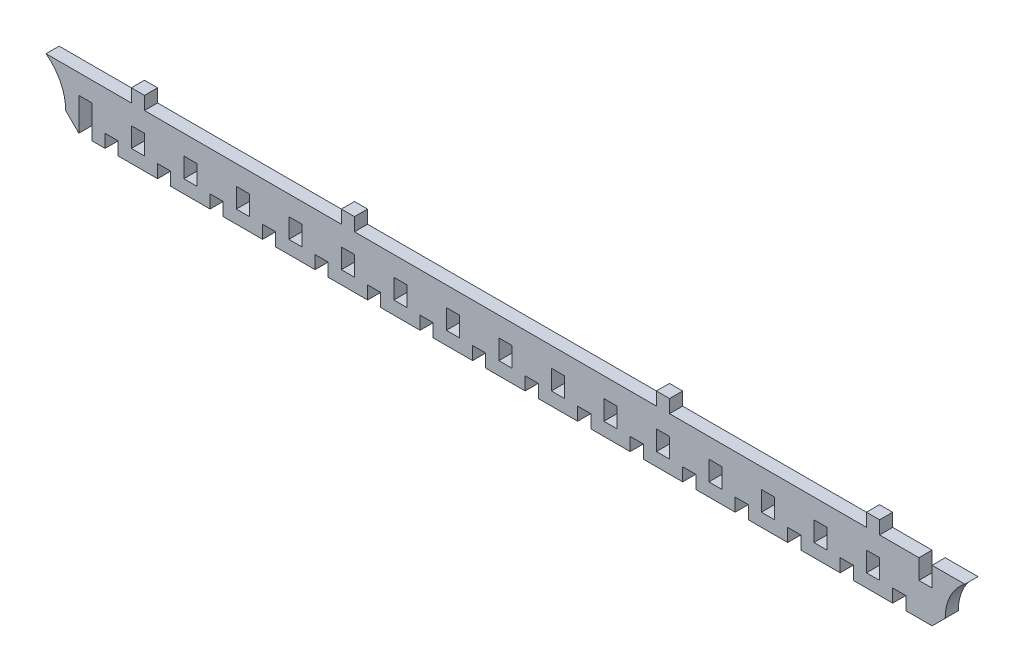
SolidWorks part; units mm, degrees
ref_plane "Front Plane" through (0, 0, 0) normal (0, 0, 1) x (1, 0, 0)
ref_plane "Top Plane" through (0, 0, 0) normal (0, 1, 0) x (1, 0, 0)
ref_plane "Right Plane" through (0, 0, 0) normal (1, 0, 0) x (0, 0, -1)
sketch "Sketch1" plane through (0, 0, 0) normal (0, 0, 1) x (1, 0, 0)
  line L151 (25.5, 6) -> (25.5, 10.5)
  line L152 (25.5, 10.5) -> (22.5, 10.5)
  line L153 (22.5, 10.5) -> (22.5, 6)
  line L154 (22.5, 6) -> (25.5, 6)
  line L155 (37.5, 6) -> (37.5, 10.5)
  line L156 (37.5, 10.5) -> (34.5, 10.5)
  line L157 (34.5, 10.5) -> (34.5, 6)
  line L158 (34.5, 6) -> (37.5, 6)
  line L159 (49.5, 6) -> (49.5, 10.5)
  line L160 (49.5, 10.5) -> (46.5, 10.5)
  line L161 (46.5, 10.5) -> (46.5, 6)
  line L162 (46.5, 6) -> (49.5, 6)
  line L163 (61.5, 6) -> (61.5, 10.5)
  line L164 (61.5, 10.5) -> (58.5, 10.5)
  line L165 (58.5, 10.5) -> (58.5, 6)
  line L166 (58.5, 6) -> (61.5, 6)
  line L167 (73.5, 6) -> (73.5, 10.5)
  line L168 (73.5, 10.5) -> (70.5, 10.5)
  line L169 (70.5, 10.5) -> (70.5, 6)
  line L170 (70.5, 6) -> (73.5, 6)
  line L171 (85.5, 6) -> (85.5, 10.5)
  line L172 (85.5, 10.5) -> (82.5, 10.5)
  line L173 (82.5, 10.5) -> (82.5, 6)
  line L174 (82.5, 6) -> (85.5, 6)
  line L175 (97.5, 6) -> (97.5, 10.5)
  line L176 (97.5, 10.5) -> (94.5, 10.5)
  line L177 (94.5, 10.5) -> (94.5, 6)
  line L178 (94.5, 6) -> (97.5, 6)
  line L179 (109.5, 6) -> (109.5, 10.5)
  line L180 (109.5, 10.5) -> (106.5, 10.5)
  line L181 (106.5, 10.5) -> (106.5, 6)
  line L182 (106.5, 6) -> (109.5, 6)
  line L183 (121.5, 6) -> (121.5, 10.5)
  line L184 (121.5, 10.5) -> (118.5, 10.5)
  line L185 (118.5, 10.5) -> (118.5, 6)
  line L186 (118.5, 6) -> (121.5, 6)
  line L187 (133.5, 6) -> (133.5, 10.5)
  line L188 (133.5, 10.5) -> (130.5, 10.5)
  line L189 (130.5, 10.5) -> (130.5, 6)
  line L190 (130.5, 6) -> (133.5, 6)
  line L191 (145.5, 6) -> (145.5, 10.5)
  line L192 (145.5, 10.5) -> (142.5, 10.5)
  line L193 (142.5, 10.5) -> (142.5, 6)
  line L194 (142.5, 6) -> (145.5, 6)
  line L195 (157.5, 6) -> (157.5, 10.5)
  line L196 (157.5, 10.5) -> (154.5, 10.5)
  line L197 (154.5, 10.5) -> (154.5, 6)
  line L198 (154.5, 6) -> (157.5, 6)
  line L199 (169.5, 6) -> (169.5, 10.5)
  line L200 (169.5, 10.5) -> (166.5, 10.5)
  line L201 (166.5, 10.5) -> (166.5, 6)
  line L202 (166.5, 6) -> (169.5, 6)
  line L203 (181.5, 6) -> (181.5, 10.5)
  line L204 (181.5, 10.5) -> (178.5, 10.5)
  line L205 (178.5, 10.5) -> (178.5, 6)
  line L206 (178.5, 6) -> (181.5, 6)
  line L207 (193.5, 6) -> (193.5, 10.5)
  line L208 (193.5, 10.5) -> (190.5, 10.5)
  line L209 (190.5, 10.5) -> (190.5, 6)
  line L210 (190.5, 6) -> (193.5, 6)
  line L211 (187.5, 3) -> (187.5, 6)
  line L212 (187.5, 6) -> (184.5, 6)
  line L213 (184.5, 6) -> (184.5, 3)
  line L214 (184.5, 3) -> (175.5, 3)
  line L215 (175.5, 3) -> (175.5, 6)
  line L216 (175.5, 6) -> (172.5, 6)
  line L217 (172.5, 6) -> (172.5, 3)
  line L218 (172.5, 3) -> (163.5, 3)
  line L219 (163.5, 3) -> (163.5, 6)
  line L220 (163.5, 6) -> (160.5, 6)
  line L221 (160.5, 6) -> (160.5, 3)
  line L222 (160.5, 3) -> (151.5, 3)
  line L223 (151.5, 3) -> (151.5, 6)
  line L224 (151.5, 6) -> (148.5, 6)
  line L225 (148.5, 6) -> (148.5, 3)
  line L226 (148.5, 3) -> (139.5, 3)
  line L227 (139.5, 3) -> (139.5, 6)
  line L228 (139.5, 6) -> (136.5, 6)
  line L229 (136.5, 6) -> (136.5, 3)
  line L230 (136.5, 3) -> (127.5, 3)
  line L231 (127.5, 3) -> (127.5, 6)
  line L232 (127.5, 6) -> (124.5, 6)
  line L233 (124.5, 6) -> (124.5, 3)
  line L234 (124.5, 3) -> (115.5, 3)
  line L235 (115.5, 3) -> (115.5, 6)
  line L236 (115.5, 6) -> (112.5, 6)
  line L237 (112.5, 6) -> (112.5, 3)
  line L238 (112.5, 3) -> (103.5, 3)
  line L239 (103.5, 3) -> (103.5, 6)
  line L240 (103.5, 6) -> (100.5, 6)
  line L241 (100.5, 6) -> (100.5, 3)
  line L242 (100.5, 3) -> (91.5, 3)
  line L243 (91.5, 3) -> (91.5, 6)
  line L244 (91.5, 6) -> (88.5, 6)
  line L245 (88.5, 6) -> (88.5, 3)
  line L246 (88.5, 3) -> (79.5, 3)
  line L247 (79.5, 3) -> (79.5, 6)
  line L248 (79.5, 6) -> (76.5, 6)
  line L249 (76.5, 6) -> (76.5, 3)
  line L250 (76.5, 3) -> (67.5, 3)
  line L251 (67.5, 3) -> (67.5, 6)
  line L252 (67.5, 6) -> (64.5, 6)
  line L253 (64.5, 6) -> (64.5, 3)
  line L254 (64.5, 3) -> (55.5, 3)
  line L255 (55.5, 3) -> (55.5, 6)
  line L256 (55.5, 6) -> (52.5, 6)
  line L257 (52.5, 6) -> (52.5, 3)
  line L258 (52.5, 3) -> (43.5, 3)
  line L259 (43.5, 3) -> (43.5, 6)
  line L260 (43.5, 6) -> (40.5, 6)
  line L261 (40.5, 6) -> (40.5, 3)
  line L262 (40.5, 3) -> (31.5, 3)
  line L263 (31.5, 3) -> (31.5, 6)
  line L264 (31.5, 6) -> (28.5, 6)
  line L265 (28.5, 6) -> (28.5, 3)
  line L266 (28.5, 3) -> (19.5, 3)
  line L267 (19.5, 3) -> (19.5, 6)
  line L268 (19.5, 6) -> (16.5, 6)
  line L269 (16.5, 6) -> (16.5, 3)
  line L270 (16.5, 3) -> (13.5, 3)
  line L271 (13.5, 3) -> (13.5, 10.5)
  line L272 (13.5, 10.5) -> (10.5, 10.5)
  line L273 (10.5, 10.5) -> (10.5, 3)
  line L274 (10.5, 3) -> (7.5, 6)
  line L275 (3, 15) -> (22.5, 15)
  line L276 (22.5, 15) -> (22.5, 18)
  line L277 (22.5, 18) -> (25.5, 18)
  line L278 (25.5, 18) -> (25.5, 15)
  line L279 (25.5, 15) -> (70.5, 15)
  line L280 (70.5, 15) -> (70.5, 18)
  line L281 (70.5, 18) -> (73.5, 18)
  line L282 (73.5, 18) -> (73.5, 15)
  line L283 (73.5, 15) -> (142.5, 15)
  line L284 (142.5, 15) -> (142.5, 18)
  line L285 (142.5, 18) -> (145.5, 18)
  line L286 (145.5, 18) -> (145.5, 15)
  line L287 (145.5, 15) -> (190.5, 15)
  line L288 (190.5, 15) -> (190.5, 18)
  line L289 (190.5, 18) -> (193.5, 18)
  line L290 (193.5, 18) -> (193.5, 15)
  line L291 (193.5, 15) -> (202.5, 15)
  line L292 (202.5, 15) -> (202.5, 10.5)
  line L293 (202.5, 10.5) -> (205.5, 10.5)
  line L294 (205.5, 10.5) -> (205.5, 15)
  line L295 (205.5, 15) -> (213, 15)
  line L296 (208.5, 6) -> (205.5, 3)
  line L297 (205.5, 3) -> (199.5, 3)
  line L298 (199.5, 3) -> (199.5, 6)
  line L299 (199.5, 6) -> (196.5, 6)
  line L300 (196.5, 6) -> (196.5, 3)
  line L301 (196.5, 3) -> (187.5, 3)
  arc A2 (7.5, 6) -> (3, 15) centre (-3.75, 6) ccw
  arc A3 (213, 15) -> (208.5, 6) centre (219.75, 6) ccw
extrude "Boss-Extrude1" add sketch "Sketch1" along normal blind 3
